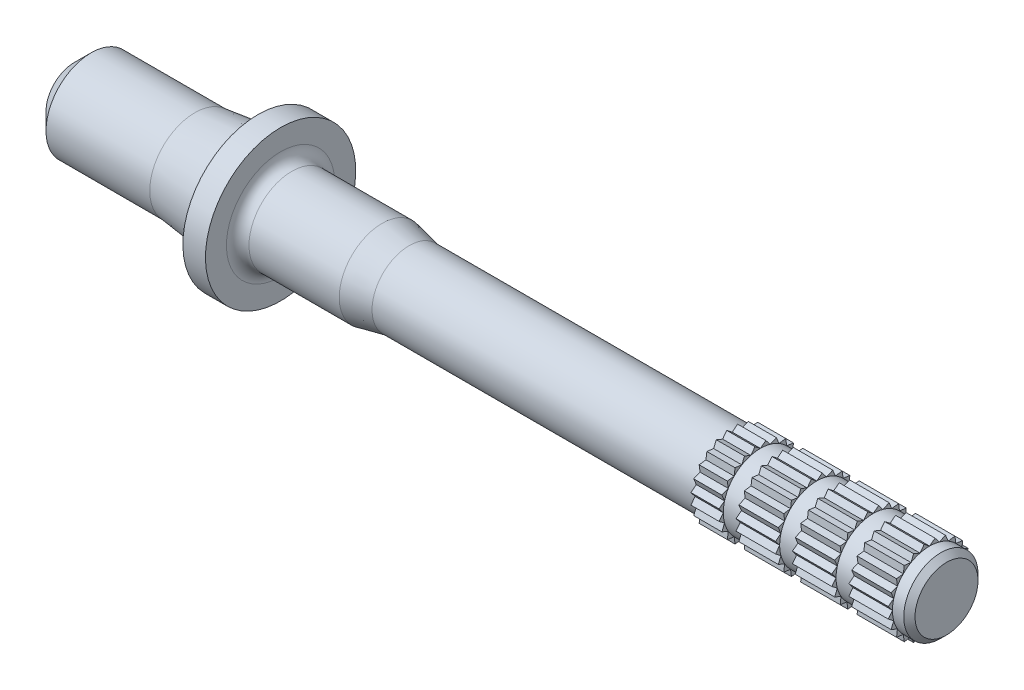
SolidWorks part; units mm, degrees
ref_plane "Front Plane" through (0, 0, 0) normal (0, 0, 1) x (1, 0, 0)
ref_plane "Top Plane" through (0, 0, 0) normal (0, 1, 0) x (1, 0, 0)
ref_plane "Right Plane" through (0, 0, 0) normal (1, 0, 0) x (0, 0, -1)
sketch "Sketch1" plane through (0, 0, 0) normal (0, 0, 1) x (1, 0, 0)
  line L0 (0, 0) -> (0, 2)
  line L1 (0, 2) -> (5.35, 2)
  line L2 (5.35, 2) -> (8.15, 2.3314)
  line L3 (8.15, 2.3314) -> (8.15, 3.3314)
  line L4 (8.15, 3.3314) -> (9.15, 3.3314)
  line L5 (9.15, 3.3314) -> (9.15, 1.9014)
  line L6 (9.15, 1.9014) -> (13.65, 1.9014)
  line L7 (13.65, 1.9014) -> (14.85, 1.6463)
  line L8 (14.85, 1.6463) -> (29.17, 1.6463)
  line L9 (29.17, 1.6463) -> (29.17, 1.85)
  line L10 (29.17, 1.85) -> (38.67, 1.85)
  line L11 (38.67, 1.85) -> (38.67, 0)
  line L12 (38.67, 0) -> (0, 0)
  dimension "D1" = 2
  dimension "D2" = 5.35
  dimension "D3" = 2.8
  dimension "D4" = 173.25
  dimension "D5" = 1
  dimension "D6" = 1
  dimension "D7" = 1.43
  dimension "D8" = 168
  dimension "D9" = 1.2
  dimension "D10" = 4.5
  dimension "D11" = 14.32
  dimension "D12" = 9.5
  dimension "D13" = 1.85
  dimension "D14" = 0.2037
revolve "Revolve1" add sketch "Sketch1" angle 360 about L12
sketch "Sketch2" plane through (38.67, 0, 0) normal (1, 0, 0) x (0, 0, -1)
  line L0 (0, 0) -> (0, 1.9014) construction
  line L1 (-0.2443, 1.8338) -> (0, 1.6463)
  line L2 (0, 1.6463) -> (0.2443, 1.8338)
  circle A0 centre (0, 0) radius 1.9014 construction
  circle A3 centre (0, 0) radius 1.85 construction
  circle A4 centre (0, 0) radius 1.6463 construction
  arc A5 (-0.2443, 1.8338) -> (0.2443, 1.8338) centre (0, 0) cw
  circle M5 centre (0, 0) radius 1.85
  dimension "D1" = 105
extrude "Cut-Extrude1" cut sketch "Sketch2" against normal up to next contours L1 L0 A5 | L0 L2 M5
pattern_circular "CirPattern1" count 24 over 360 about axis through (0, 0, 0) along (1, 0, 0) of "Cut-Extrude1"
sketch "Sketch3" plane through (38.67, 0, 0) normal (1, 0, 0) x (0, 0, -1)
  circle A0 centre (0, 0) radius 1.6463
extrude "Cut-Extrude2" cut sketch "Sketch3" against normal blind 0.75 flip side to cut
pattern_linear "LPattern1" count 4 spacing 2.5 along (-1, 0, 0) of "Cut-Extrude2"
chamfer "Chamfer1" distance 0.75 angle 45 1 edges at (0, 2, 0)
chamfer "Chamfer2" distance 0.25 angle 45 1 edges at (38.67, 1.6463, 0)
fillet "Fillet1" radius 0.5 2 edges at (8.15, 2.3314, 0) (9.15, 1.9014, 0)
